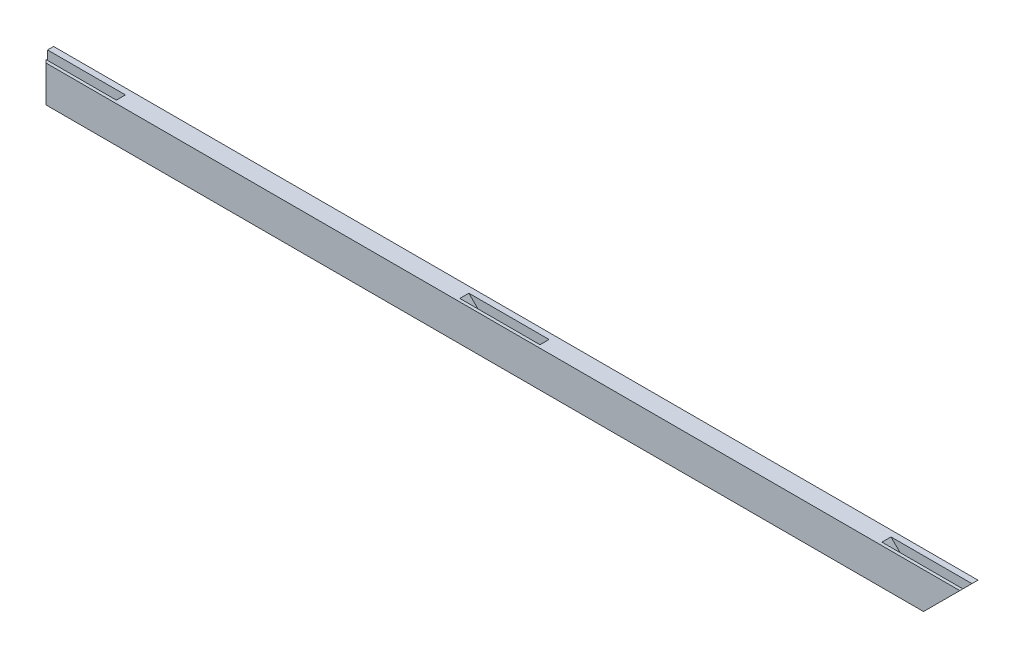
SolidWorks part; units mm, degrees
ref_plane "前视基准面" through (0, 0, 0) normal (0, 0, 1) x (1, 0, 0)
ref_plane "上视基准面" through (0, 0, 0) normal (0, 1, 0) x (1, 0, 0)
ref_plane "右视基准面" through (0, 0, 0) normal (1, 0, 0) x (0, 0, -1)
sketch "草图1" plane through (0, 0, 0) normal (0, 0, 1) x (1, 0, 0)
  line L0 (0, 12) -> (0, -12)
  line L1 (0, -12) -> (587, -12)
  line L2 (587, -12) -> (611, 12)
  line L3 (611, 12) -> (0, 12)
  dimension "D1" = 24
  dimension "D2" = 611
  dimension "D3" = 45
extrude "凸台-拉伸1" add sketch "草图1" along normal blind 12
sketch "草图2" plane through (0, 0, 12) normal (0, 0, 1) x (1, 0, 0)
  line L0 (278.5, 12) -> (285, 5.5)
  line L1 (611, 12) -> (0, 12) construction
  line L2 (285, 5.5) -> (325, 5.5)
  line L3 (325, 5.5) -> (331.5, 12)
  line L4 (331.5, 12) -> (278.5, 12)
  line L5 (0, 12) -> (0, -12) construction
  point P6 (269.7934, 12)
  point P7 (305, 5.5)
  dimension "D1" = 40
  dimension "D2" = 6.5
  dimension "D3" = 45
  dimension "D4" = 45
  dimension "D5" = 305
extrude "切除-拉伸1" cut sketch "草图2" against normal blind 6 from offset 2 offset against normal yes
chamfer "倒角1" distance 7 1 edges at (0, 0, 12)
mirror "镜向1" about plane through (0, 0, 0) normal (0, 1, 0) of "切除-拉伸1"
sketch "草图3" plane through (0, 0, 12) normal (0, 0, 1) x (1, 0, 0)
  line L0 (593.5, -5.5) -> (587, -12)
  line L1 (587, -12) -> (611, 12) construction
  line L2 (587, -12) -> (557.5, -12)
  line L3 (7, -12) -> (587, -12) construction
  line L4 (557.5, -12) -> (564, -5.5)
  line L5 (564, -5.5) -> (593.5, -5.5)
  line L6 (611, 12) -> (604.5, 5.5)
  line L7 (604.5, 5.5) -> (564, 5.5)
  line L8 (564, 5.5) -> (557.5, 12)
  line L9 (611, 12) -> (7, 12) construction
  line L10 (557.5, 12) -> (611, 12)
  line L11 (0, 12) -> (0, 5.5)
  line L12 (0, -12) -> (0, 12) construction
  line L13 (0, 5.5) -> (45, 5.5)
  line L14 (45, 5.5) -> (51.5, 12)
  line L15 (51.5, 12) -> (0, 12)
  line L16 (0, -12) -> (0, -5.5)
  line L17 (7, -12) -> (0, -12) construction
  line L18 (0, -5.5) -> (45, -5.5)
  line L19 (45, -5.5) -> (51.5, -12)
  line L20 (51.5, -12) -> (0, -12)
  dimension "D1" = 6.5
  dimension "D2" = 23
  dimension "D3" = 6.5
  dimension "D4" = 47
  dimension "D5" = 45
  dimension "D6" = 6.5
  dimension "D7" = 6.5
  dimension "D8" = 45
  dimension "D9" = 45
  dimension "D10" = 45
  dimension "D11" = 45
extrude "切除-拉伸2" cut sketch "草图3" against normal blind 6 from offset 2
